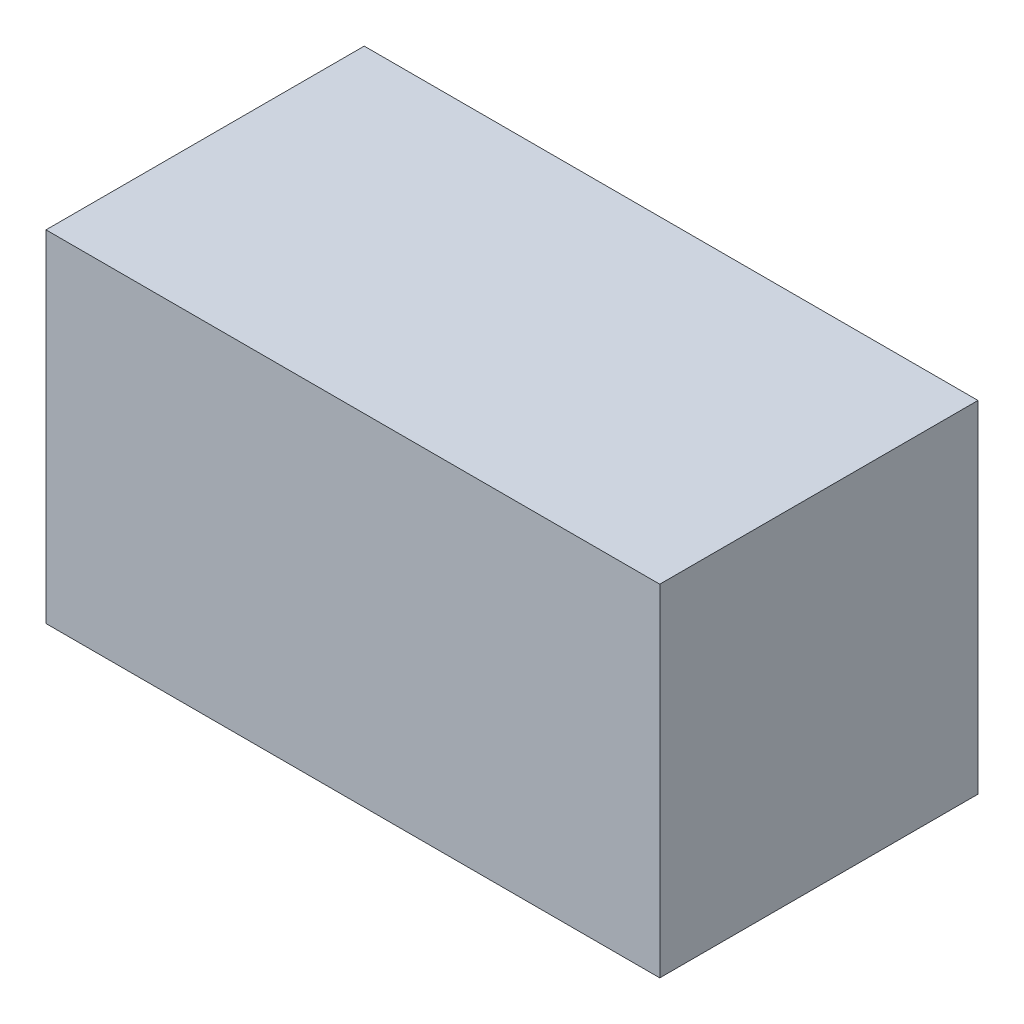
SolidWorks part; units mm, degrees
ref_plane "Спереди" through (0, 0, 0) normal (0, 0, 1) x (1, 0, 0)
ref_plane "Сверху" through (0, 0, 0) normal (0, 1, 0) x (1, 0, 0)
ref_plane "Справа" through (0, 0, 0) normal (1, 0, 0) x (0, 0, -1)
sketch "MASTER_FOOTPRINT" plane through (0, 0, 0) normal (0, 1, 0) x (1, 0, 0)
  line L1 (0, 0) -> (1350, 0)
  line L2 (0, 0) -> (0, 700)
  line L3 (0, 700) -> (1350, 700)
  line L4 (1350, 0) -> (1350, 700)
  dimension "D1" = 1350
  dimension "D2" = 700
extrude "BATH_BASE_PLATE" add sketch "MASTER_FOOTPRINT" along normal blind 750
equation "\"AI_Q_Peak\"= 0.006"
equation "\"AI_B_Bath\" = 700"
equation "\"AI_L_Settle\" = 900"
equation "\"AI_L_Inlet\"= 250"
equation "\"AI_L_Outlet\"= 200"
equation "\"AI_L_Bath\" = 1350"
equation "\"AI_H_Water\"= 550"
equation "\"AI_H_Freeboard\"= 200"
equation "\"AI_H_Bath\"= 750"
equation "\"AI_Shell_Thickness\"= 2"
equation "\"AI_Inlet_DN\"= 100"
equation "\"AI_Weir_Width\"= 600"
equation "\"AI_Inlet_Baffle_Offset\"= 125"
equation "\"AI_Distributor_Open_Area\"= 0.28"
equation "\"AI_Distributor_Hole_Dia\"= 22"
equation "\"AI_Distributor_Blind_Zone\"= 110"
equation "\"AI_Outlet_Baffle_Depth\"= 250"
equation "\"AI_Screw_Diameter\"= 100"
equation "\"AI_Screw_Pitch\"= 100"
equation "\"AI_Screw_Angle\"= 30"
equation "\"AI_Screw_Rpm\"= 15"
equation "\"AI_Screw_Clearance\"= 5"
equation "\"AI_Liner_Thickness\"= 5"
equation "\"AI_Discharge_Height\"= 650"
equation "\"AI_Frame_Height\"= 500"
equation "\"D1@MASTER_FOOTPRINT\" = \"AI_L_Bath\""
equation "\"D2@MASTER_FOOTPRINT\" = \"AI_B_Bath\""
equation "\"D1@BATH_BASE_PLATE\" = \"AI_H_Bath\""
